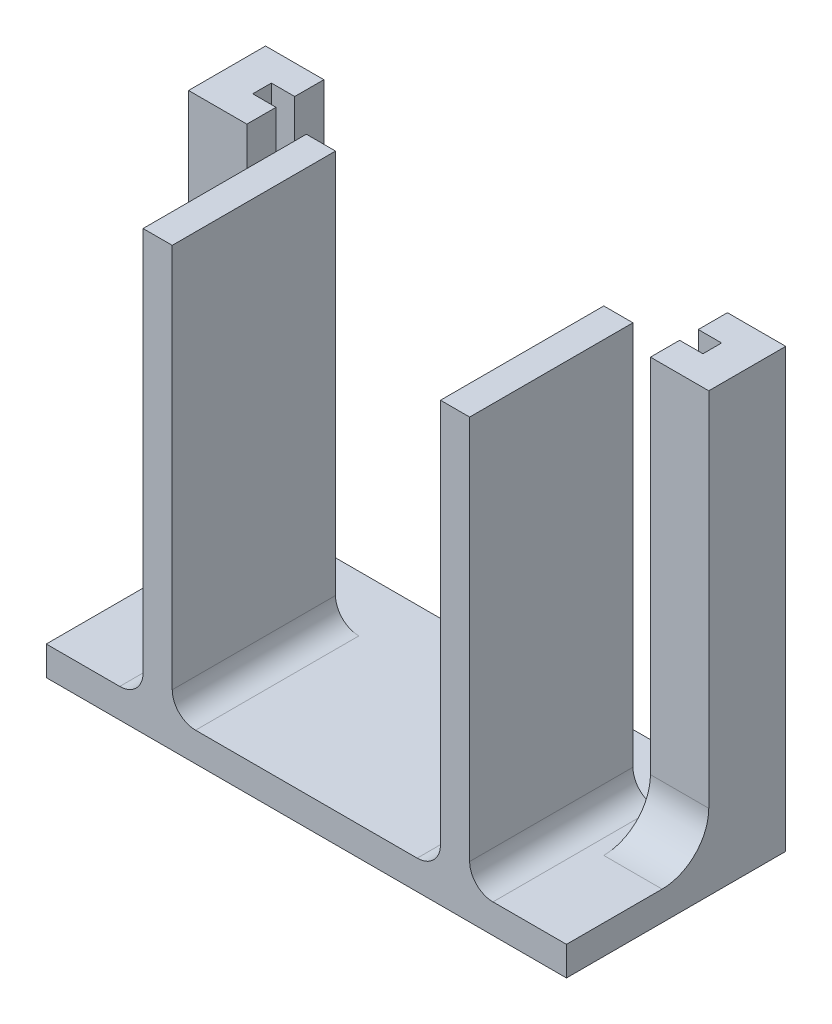
SolidWorks part; units mm, degrees
ref_plane "Front Plane" through (0, 0, 0) normal (0, 0, 1) x (1, 0, 0)
ref_plane "Top Plane" through (0, 0, 0) normal (0, 1, 0) x (1, 0, 0)
ref_plane "Right Plane" through (0, 0, 0) normal (1, 0, 0) x (0, 0, -1)
ref_plane "Plane1" through (0, -19, 0) normal (0, 1, 0) x (1, 0, 0)
sketch "Sketch1" plane through (0, -19, 0) normal (0, 1, 0) x (1, 0, 0)
  line L0 (0, 0) -> (0, -21.3085) construction
  line L1 (-19.3, 0.3) -> (-17.3, 0.3)
  line L2 (-17.3, 0.3) -> (-17.3, 2.8)
  line L3 (-17.3, 2.8) -> (-22.3, 2.8)
  line L4 (-22.3, 2.8) -> (-22.3, -3.8)
  line L5 (-22.3, -3.8) -> (-17.3, -3.8)
  line L6 (-17.3, -3.8) -> (-17.3, -1.3)
  line L7 (-17.3, -1.3) -> (-19.3, -1.3)
  line L8 (-19.3, -1.3) -> (-19.3, 0.3)
  line L10 (19.3, -1.3) -> (19.3, 0.3)
  line L11 (17.3, -1.3) -> (19.3, -1.3)
  line L12 (17.3, -3.8) -> (17.3, -1.3)
  line L13 (22.3, -3.8) -> (17.3, -3.8)
  line L14 (22.3, 2.8) -> (22.3, -3.8)
  line L15 (17.3, 2.8) -> (22.3, 2.8)
  line L16 (17.3, 0.3) -> (17.3, 2.8)
  line L17 (19.3, 0.3) -> (17.3, 0.3)
  line L18 (11.5, -2) -> (11.5, -16)
  line L19 (-14, -2) -> (-11.5, -2)
  line L20 (-14, -2) -> (-14, -16)
  line L21 (-14, -16) -> (-11.5, -16)
  line L22 (-11.5, -2) -> (-11.5, -16)
  line L23 (14, -16) -> (11.5, -16)
  line L24 (14, -2) -> (14, -16)
  line L25 (14, -2) -> (11.5, -2)
  dimension "D1" = 2
  dimension "D2" = 17.3
  dimension "D3" = 5
  dimension "D4" = 2.5
  dimension "D5" = 0.3
  dimension "D6" = 1.6
  dimension "D7" = 6.6
  dimension "D8" = 14
  dimension "D9" = 2
  dimension "D10" = 2.5
  dimension "D11" = 11.5
extrude "Boss-Extrude1" add sketch "Sketch1" along normal blind 35
sketch "Sketch2" plane through (0, -19, 0) normal (0, 1, 0) x (1, 0, 0)
  line L1 (-22.3, 2.8) -> (22.3, 2.8)
  line L2 (-22.3, 2.8) -> (-22.3, -16)
  line L3 (-22.3, -16) -> (22.3, -16)
  line L4 (22.3, 2.8) -> (22.3, -16)
  dimension "D1" = 44.6
  dimension "D2" = 18.8
extrude "Boss-Extrude2" add sketch "Sketch2" against normal blind 2.5
fillet "Fillet1" radius 2 4 edges at (-14, -19, 9) (11.5, -19, 9) (-11.5, -19, 9) (14, -19, 9)
fillet "Fillet2" radius 4 2 edges at (19.8, -19, 3.8) (-19.8, -19, 3.8)
